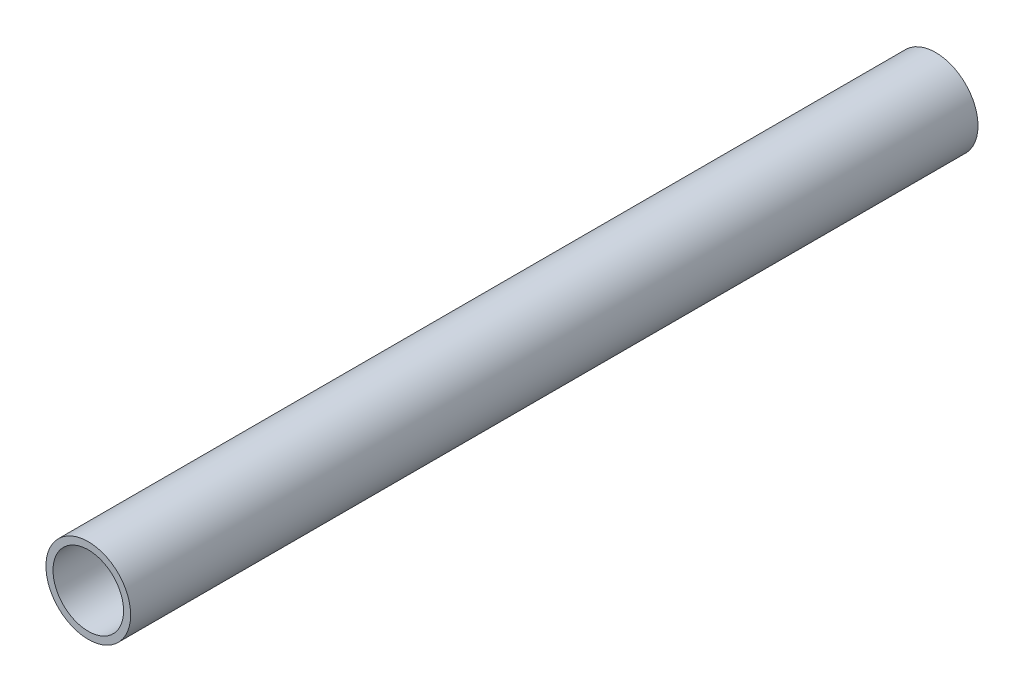
SolidWorks part; units mm, degrees
ref_plane "Front Plane" through (0, 0, 0) normal (0, 0, 1) x (1, 0, 0)
ref_plane "Top Plane" through (0, 0, 0) normal (0, 1, 0) x (1, 0, 0)
ref_plane "Right Plane" through (0, 0, 0) normal (1, 0, 0) x (0, 0, -1)
sketch "Sketch1" plane through (0, 0, 0) normal (0, 0, 1) x (1, 0, 0)
  circle A0 centre (0, 0) radius 12.5
  circle A1 centre (0, 0) radius 15
  dimension "D1" = 30
  dimension "D2" = 25
extrude "Boss-Extrude1" add sketch "Sketch1" along normal blind 300
